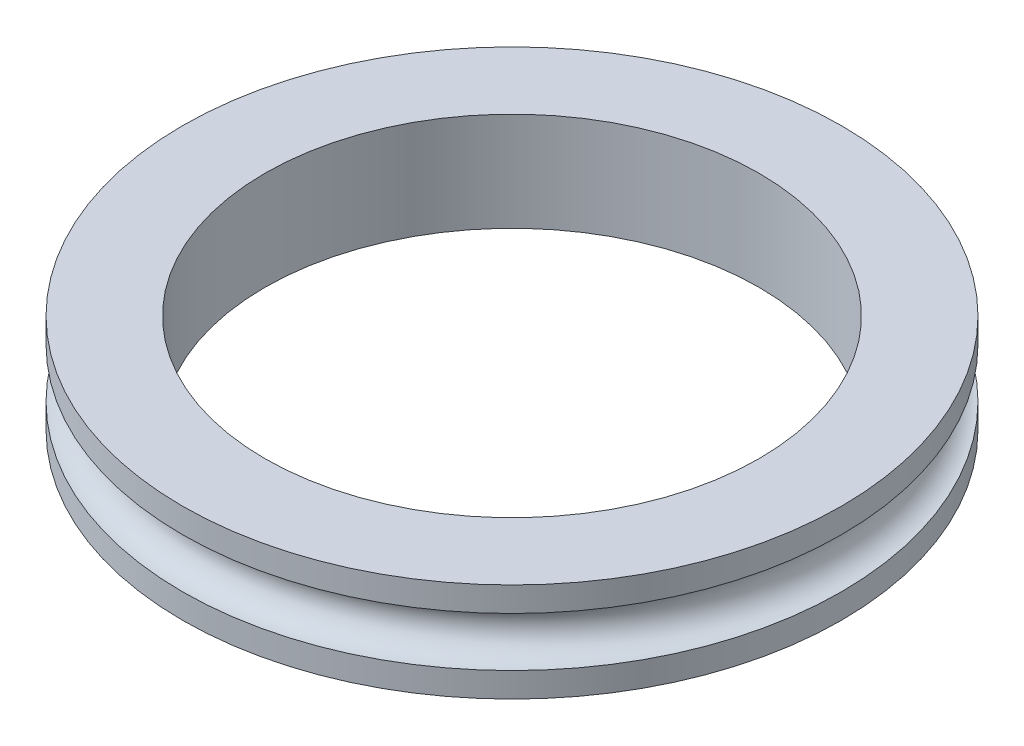
SolidWorks part; units mm, degrees
ref_plane "Alzado" through (0, 0, 0) normal (0, 0, 1) x (1, 0, 0)
ref_plane "Planta" through (0, 0, 0) normal (0, 1, 0) x (1, 0, 0)
ref_plane "Vista lateral" through (0, 0, 0) normal (1, 0, 0) x (0, 0, -1)
sketch "Croquis1" plane through (0, 0, 0) normal (0, 1, 0) x (1, 0, 0)
  circle A0 centre (0, 0) radius 10
  dimension "D1" = 20
extrude "Saliente-Extruir1" add sketch "Croquis1" along normal blind 3
ref_axis "Eje1" through (0, 3, 0) along (0, -1, 0)
sketch "Croquis2" plane through (0, 0, 0) normal (1, 0, 0) x (0, 0, -1)
  line L0 (10, 0) -> (10, 3) construction
  circle A0 centre (10, 1.5) radius 0.75
  dimension "D1" = 1.5
revolve "Cortar-Revolución1" cut sketch "Croquis2" angle 360 about axis through (0, 3, 0) along (0, -1, 0)
sketch "Croquis4" plane through (0, 0, 0) normal (0, -1, 0) x (1, 0, 0)
  circle A0 centre (0, 0) radius 7.5
  dimension "D1" = 15
extrude "Cortar-Extruir1" cut sketch "Croquis4" against normal through all
